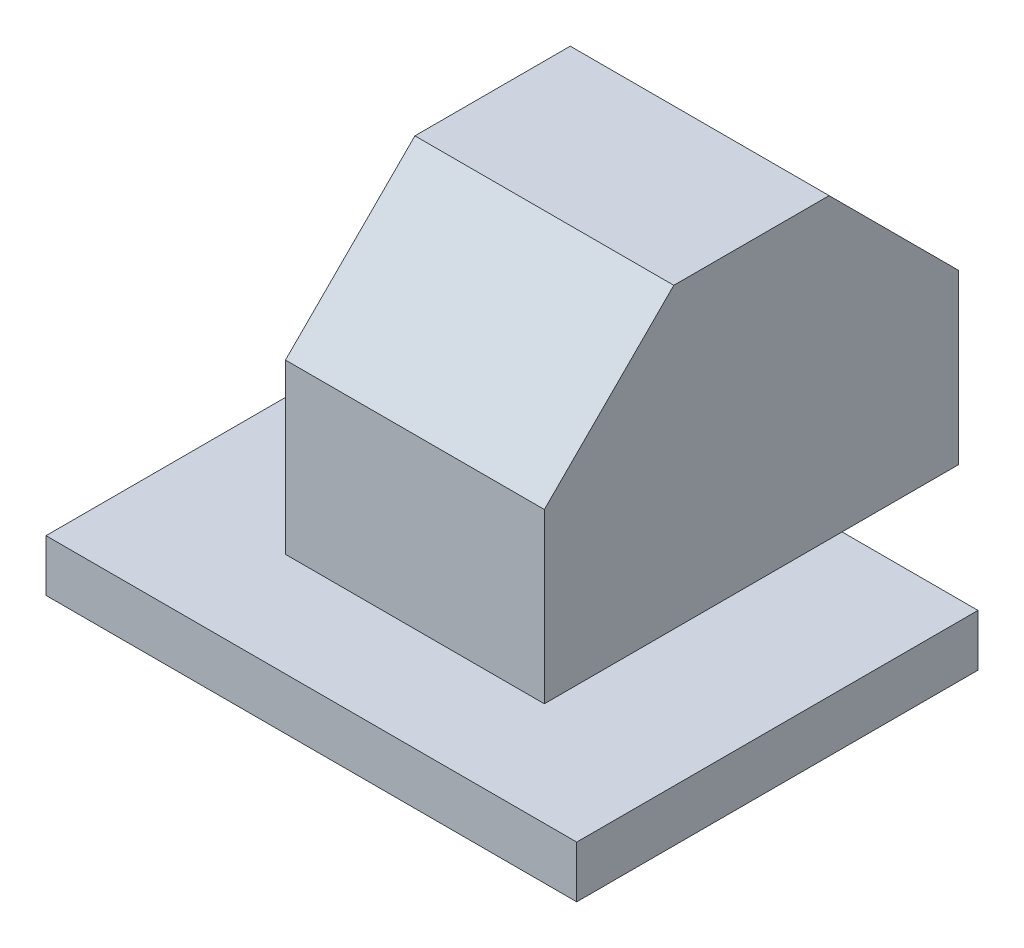
SolidWorks part; units mm, degrees
ref_plane "Front Plane" through (0, 0, 0) normal (0, 0, 1) x (1, 0, 0)
ref_plane "Top Plane" through (0, 0, 0) normal (0, 1, 0) x (1, 0, 0)
ref_plane "Right Plane" through (0, 0, 0) normal (1, 0, 0) x (0, 0, -1)
sketch "Sketch1" plane through (0, 0, 0) normal (0, 1, 0) x (1, 0, 0)
  line L1 (10.25, 7.75) -> (-10.25, 7.75)
  line L2 (10.25, 7.75) -> (10.25, -7.75)
  line L3 (10.25, -7.75) -> (-10.25, -7.75)
  line L4 (-10.25, 7.75) -> (-10.25, -7.75)
  line L5 (10.25, 7.75) -> (-10.25, -7.75) construction
  line L6 (10.25, -7.75) -> (-10.25, 7.75) construction
  point P0 (0, 0)
  dimension "D1" = 20.5
  dimension "D2" = 15.5
extrude "Boss-Extrude1" add sketch "Sketch1" along normal blind 2
sketch "Sketch3" plane through (0, 2, 0) normal (0, 1, 0) x (1, 0, 0)
  line L1 (5, -3.75) -> (-5, -3.75)
  line L2 (5, -3.75) -> (5, 12.25)
  line L3 (5, 12.25) -> (-5, 12.25)
  line L4 (-5, -3.75) -> (-5, 12.25)
  line L5 (5, -3.75) -> (-5, 12.25) construction
  line L6 (5, 12.25) -> (-5, -3.75) construction
  line L7 (10.25, 7.75) -> (-10.25, 7.75) construction
  point P0 (0, 4.25)
  dimension "D1" = 10
  dimension "D2" = 16
  dimension "D3" = 4.5
extrude "Boss-Extrude3" add sketch "Sketch3" along normal blind 11.5
sketch "Sketch4" plane through (0, 2, 0) normal (0, 1, 0) x (1, 0, 0)
  circle A0 centre (-8.6444, 4.9812) radius 1.4381
extrude "Boss-Extrude5" add sketch "Sketch4" along normal blind 1.5
chamfer "Chamfer1" distance 5 angle 45 2 edges at (0, 13.5, 3.75) (0, 13.5, -12.25)
